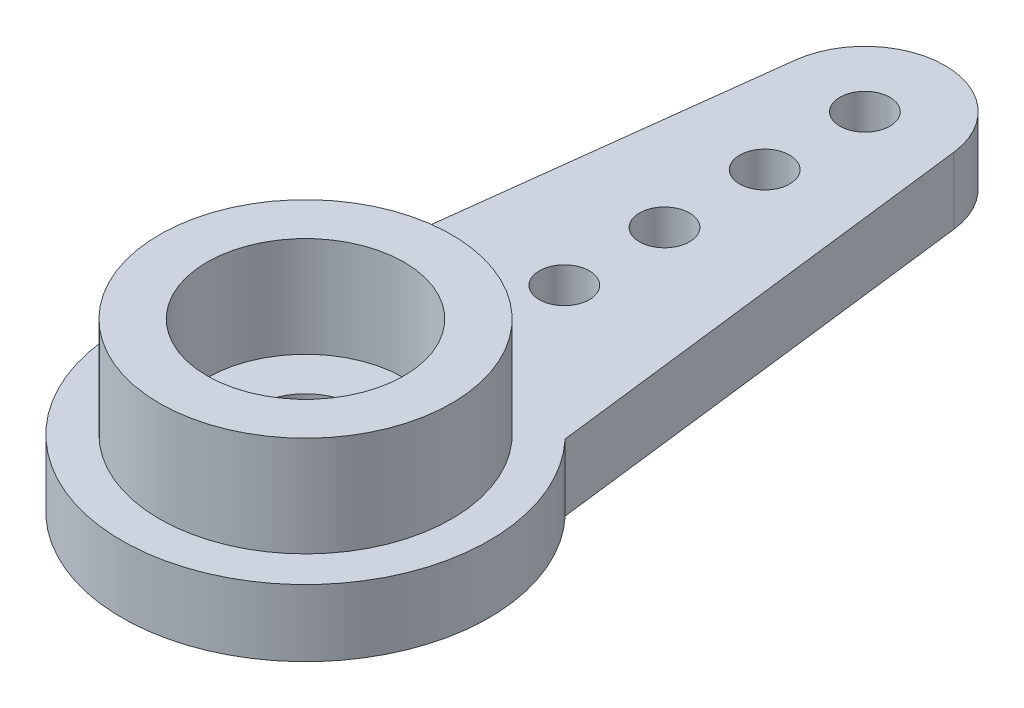
SolidWorks part; units mm, degrees
ref_plane "Alzado" through (0, 0, 0) normal (0, 0, 1) x (1, 0, 0)
ref_plane "Planta" through (0, 0, 0) normal (0, 1, 0) x (1, 0, 0)
ref_plane "Vista lateral" through (0, 0, 0) normal (1, 0, 0) x (0, 0, -1)
sketch "Croquis1" plane through (0, 0, 0) normal (0, 1, 0) x (1, 0, 0)
  line L0 (0, 0) -> (0, 16.75) construction
  line L1 (-4, 3.7749) -> (4, 3.7749) construction
  line L2 (-4, 3.7749) -> (-2.3824, 17.0405)
  line L3 (4, 3.7749) -> (2.3824, 17.0405)
  arc A0 (-4, 3.7749) -> (4, 3.7749) centre (0, 0) ccw
  arc A2 (2.3824, 17.0405) -> (-2.3824, 17.0405) centre (0, 16.75) ccw
  circle A3 centre (0, 16.75) radius 0.75
  circle A4 centre (0, 13.75) radius 0.75
  circle A5 centre (0, 10.75) radius 0.75
  circle A6 centre (0, 7.75) radius 0.75
  circle A7 centre (0, 0) radius 1.5
  dimension "D2" = 8
  dimension "D3" = 4.8
  dimension "D5" = 1.5
  dimension "D8" = 3
  dimension "D4" = 11
  dimension "D9" = 3
  dimension "D1" = 16.75
  dimension "D6" = 3
  dimension "D7" = 3
extrude "Saliente-Extruir1" add sketch "Croquis1" along normal blind 2
sketch "Croquis2" plane through (0, 2, 0) normal (0, 1, 0) x (1, 0, 0)
  circle A0 centre (0, 0) radius 4.375
  circle A1 centre (0, 0) radius 2.95
  dimension "D1" = 8.75
  dimension "D2" = 5.9
extrude "Saliente-Extruir2" add sketch "Croquis2" along normal blind 3
